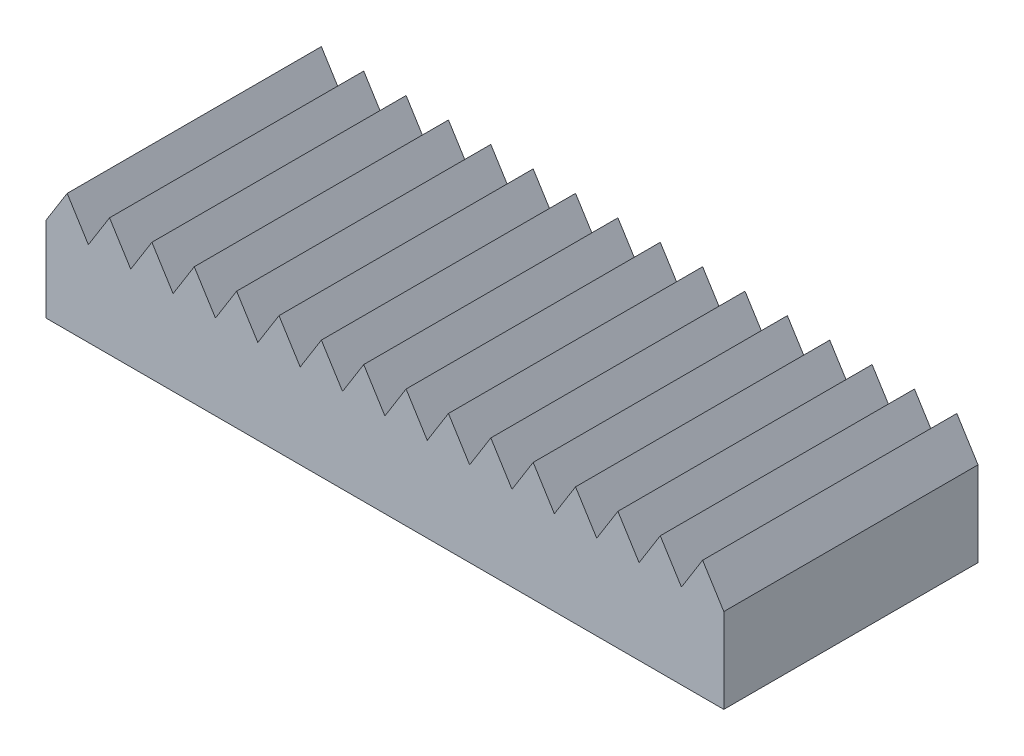
SolidWorks part; units mm, degrees
ref_plane "Front Plane" through (0, 0, 0) normal (0, 0, 1) x (1, 0, 0)
ref_plane "Top Plane" through (0, 0, 0) normal (0, 1, 0) x (1, 0, 0)
ref_plane "Right Plane" through (0, 0, 0) normal (1, 0, 0) x (0, 0, -1)
sketch "Sketch1" plane through (0, 0, 0) normal (0, 0, 1) x (1, 0, 0)
  line L2 (0, 0) -> (0, -5)
  line L3 (0, -5) -> (40, -5)
  line L4 (40, 0) -> (40, -5)
  line L7 (2.5, 0) -> (1.25, 2)
  line L8 (1.25, 2) -> (0, 0)
  line L10 (5, 0) -> (3.75, 2)
  line L11 (3.75, 2) -> (2.5, 0)
  line L13 (7.5, 0) -> (6.25, 2)
  line L14 (6.25, 2) -> (5, 0)
  line L16 (10, 0) -> (8.75, 2)
  line L17 (8.75, 2) -> (7.5, 0)
  line L19 (12.5, 0) -> (11.25, 2)
  line L20 (11.25, 2) -> (10, 0)
  line L22 (15, 0) -> (13.75, 2)
  line L23 (13.75, 2) -> (12.5, 0)
  line L25 (17.5, 0) -> (16.25, 2)
  line L26 (16.25, 2) -> (15, 0)
  line L28 (20, 0) -> (18.75, 2)
  line L29 (18.75, 2) -> (17.5, 0)
  line L31 (22.5, 0) -> (21.25, 2)
  line L32 (21.25, 2) -> (20, 0)
  line L34 (25, 0) -> (23.75, 2)
  line L35 (23.75, 2) -> (22.5, 0)
  line L37 (27.5, 0) -> (26.25, 2)
  line L38 (26.25, 2) -> (25, 0)
  line L40 (30, 0) -> (28.75, 2)
  line L41 (28.75, 2) -> (27.5, 0)
  line L43 (32.5, 0) -> (31.25, 2)
  line L44 (31.25, 2) -> (30, 0)
  line L46 (35, 0) -> (33.75, 2)
  line L47 (33.75, 2) -> (32.5, 0)
  line L49 (37.5, 0) -> (36.25, 2)
  line L50 (36.25, 2) -> (35, 0)
  line L52 (40, 0) -> (38.75, 2)
  line L53 (38.75, 2) -> (37.5, 0)
  dimension "D1" = 5
  dimension "D2" = 40
  dimension "D3" = 2.5
  dimension "D4" = 2
  dimension "D5" = 16
extrude "Boss-Extrude1" add sketch "Sketch1" along normal blind 15 contours L52 L53 L49 L50 L46 L47 L43 L44 L40 L41 L37 L38 L34 L35 L31 L32 L28 L29 L25 L26 L22 L23 L19 L20 L16 L17 L13 L14 L10 L11 L7 L8 L2 L3 L4
